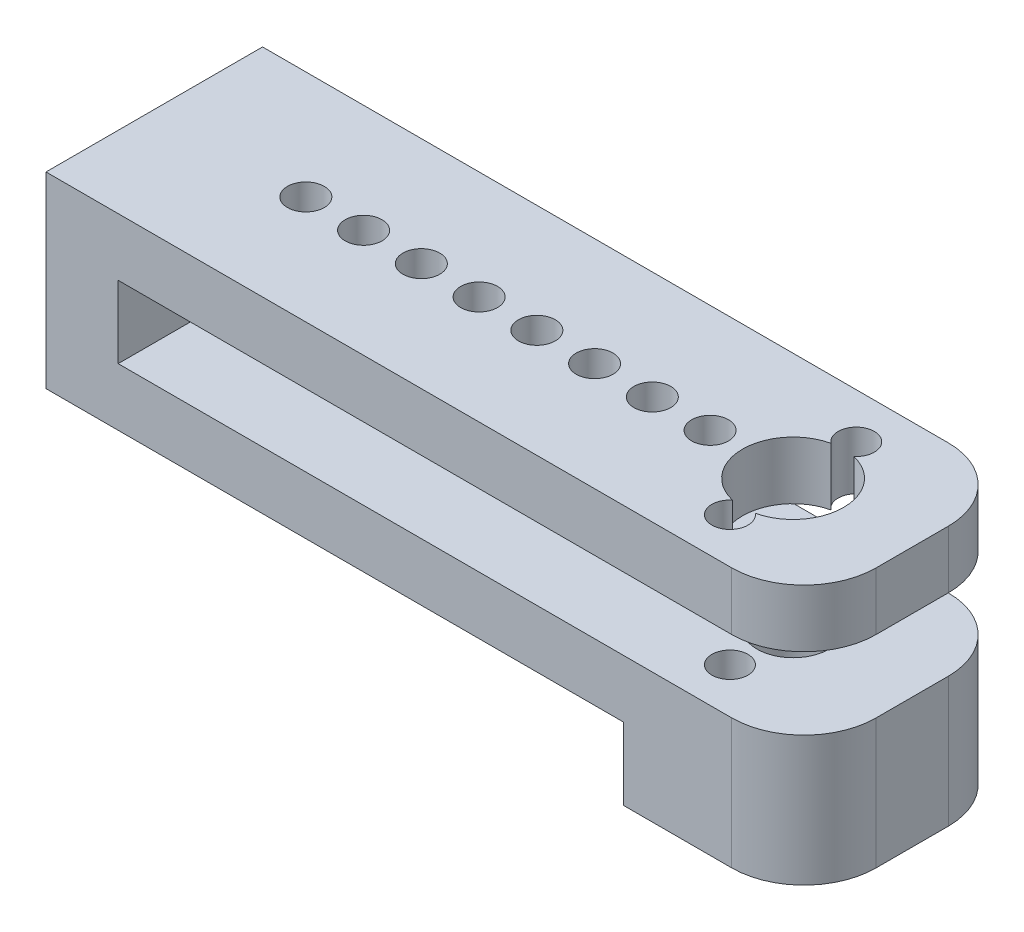
SolidWorks part; units mm, degrees
ref_plane "Front Plane" through (0, 0, 0) normal (0, 0, 1) x (1, 0, 0)
ref_plane "Top Plane" through (0, 0, 0) normal (0, 1, 0) x (1, 0, 0)
ref_plane "Right Plane" through (0, 0, 0) normal (1, 0, 0) x (0, 0, -1)
sketch "Sketch2" plane through (0, 0, 0) normal (0, 1, 0) x (1, 0, 0)
  line L1 (-72, 15) -> (3, 15)
  line L2 (-72, 15) -> (-72, -15)
  line L3 (-72, -15) -> (3, -15)
  line L4 (3, 15) -> (3, -15)
  dimension "D1" = 75
  dimension "D2" = 30
  dimension "D3" = 15
  dimension "D4" = 3
extrude "Boss-Extrude1" add sketch "Sketch2" along normal blind 8
sketch "Sketch3" plane through (0, 8, 0) normal (0, 1, 0) x (1, 0, 0)
  circle A0 centre (0, 0) radius 2.55
  dimension "D1" = 5.1
extrude "Cut-Extrude1" cut sketch "Sketch3" against normal offset from surface (7 mm away) 1 up to face at (-34.5, 0, 0)
sketch "Sketch4" plane through (0, 1, 0) normal (0, 1, 0) x (1, 0, 0)
  circle A0 centre (0, 0) radius 0.6
  dimension "D1" = 1.2
extrude "Cut-Extrude2" cut sketch "Sketch4" against normal blind 1
pattern_linear "LPattern3" count 8 spacing 8 along (-1, 0, 0) of "Cut-Extrude1", "Cut-Extrude2"
ref_plane "Plane1" through (0, -5, 0) normal (0, -1, 0) x (-1, 0, 0)
mirror "Mirror2" about plane through (0, -5, 0) normal (0, -1, 0) of bodies 122
sketch "Sketch5" plane through (-72, 0, 0) normal (-1, 0, 0) x (0, 0, 1)
  line L1 (-15, 8) -> (15, 8)
  line L2 (-15, 8) -> (-15, -18)
  line L3 (-15, -18) -> (15, -18)
  line L4 (15, 8) -> (15, -18)
extrude "Boss-Extrude2" add sketch "Sketch5" along normal blind 5 and the other way blind 5
sketch "Sketch6" plane through (3, 0, 0) normal (1, 0, 0) x (0, 0, -1)
  line L1 (-15, -10) -> (15, -10)
  line L2 (-15, -10) -> (-15, -18)
  line L3 (-15, -18) -> (15, -18)
  line L4 (15, -10) -> (15, -18)
extrude "Boss-Extrude3" add sketch "Sketch6" along normal blind 25
sketch "Sketch8" plane through (0, -18, 0) normal (0, -1, 0) x (1, 0, 0)
  line L0 (28, -15) -> (-77, -15) construction
  line L1 (28, 15) -> (3, 15)
  line L2 (28, 15) -> (28, -15)
  line L3 (28, -15) -> (3, -15)
  line L4 (3, 15) -> (3, -15)
  dimension "D1" = 25
extrude "Boss-Extrude4" add sketch "Sketch8" along normal blind 5
sketch "Sketch9" plane through (0, -23, 0) normal (0, -1, 0) x (1, 0, 0)
  line L0 (3, -15) -> (-77, -15) construction
  line L1 (28, 15) -> (-2, 15)
  line L2 (28, 15) -> (28, -15)
  line L3 (28, -15) -> (-2, -15)
  line L4 (-2, 15) -> (-2, -15)
  dimension "D1" = 30
extrude "Boss-Extrude5" add sketch "Sketch9" along normal blind 5 contours L4 L3 L2 L1
sketch "Sketch11" plane through (0, -28, 0) normal (0, -1, 0) x (1, 0, 0)
  circle A0 centre (11.5, 0) radius 11.1
  point P2 (0, 0)
  point P4 (0, 0)
  point P5 (0, 0)
  point P6 (0, 0)
  point P7 (11.2101, 2.55)
  dimension "D1" = 22.2
  dimension "D2" = 11.5
extrude "Cut-Extrude3" cut sketch "Sketch11" against normal blind 4 contours A0
sketch "Sketch13" plane through (0, -24, 0) normal (0, -1, 0) x (1, 0, 0)
  line L0 (11.5, 11.1) -> (11.5, -11.1) construction
  line L1 (0.4, 0) -> (22.6, 0) construction
  circle A0 centre (11.5, 8.75) radius 1.5
  circle A1 centre (11.5, 0) radius 11.1 construction
  circle A2 centre (11.5, 0) radius 11.1 construction
  circle A3 centre (11.5, -8.75) radius 1.5
  point P5 (0, 0)
  dimension "D1" = 3
  dimension "D2" = 17.5
extrude "Cut-Extrude4" cut sketch "Sketch13" against normal through all
sketch "Sketch16" plane through (3, 0, 0) normal (1, 0, 0) x (0, 0, -1)
  line L1 (-15, 8) -> (15, 8)
  line L2 (-15, 8) -> (-15, 0)
  line L3 (-15, 0) -> (15, 0)
  line L4 (15, 8) -> (15, 0)
extrude "Boss-Extrude6" add sketch "Sketch16" along normal blind 25
sketch "Sketch14" plane through (0, -10, 0) normal (0, 1, 0) x (1, 0, 0)
  circle A0 centre (11.5, 8.75) radius 2.5
  circle A1 centre (11.5, -8.75) radius 2.5
  dimension "D1" = 5
extrude "Cut-Extrude5" cut sketch "Sketch14" against normal offset from surface 1 and the other way through all up to face at (11.5, -24, 7.25)
sketch "Sketch15" plane through (0, -24, 0) normal (0, -1, 0) x (1, 0, 0)
  circle A0 centre (11.5, 0) radius 5
  dimension "D1" = 10
extrude "Cut-Extrude6" cut sketch "Sketch15" against normal through all
fillet "Fillet2" radius 10 2 edges at (28, -19, -15) (28, -19, 15)
fillet "Fillet3" radius 10 2 edges at (28, 4, -15) (28, 4, 15)
sketch "Sketch18" plane through (0, 8, 0) normal (0, 1, 0) x (1, 0, 0)
  circle A0 centre (11.5, 0) radius 7
  dimension "D1" = 14
extrude "Cut-Extrude7" cut sketch "Sketch18" against normal up to next contours A0
sketch "Sketch19" plane through (-67, 0, 0) normal (1, 0, 0) x (0, 0, -1)
  line L0 (-16.5, -5) -> (16.5, -5) construction
  circle A0 centre (0, -5) radius 1.5
  dimension "D1" = 3
extrude "Cut-Extrude8" cut sketch "Sketch19" against normal through all
sketch "Sketch21" plane through (-67, 0, 0) normal (1, 0, 0) x (0, 0, -1)
  line L0 (-16.5, -5) -> (16.5, -5) construction
  circle A0 centre (0, -5) radius 3.5
  dimension "D1" = 7
extrude "Cut-Extrude9" cut sketch "Sketch21" against normal blind 3
sketch "Sketch22" plane through (0, -18, 0) normal (0, -1, 0) x (1, 0, 0)
  line L1 (-2, 15) -> (3, 15)
  line L2 (-2, 15) -> (-2, -15)
  line L3 (-2, -15) -> (3, -15)
  line L4 (3, 15) -> (3, -15)
extrude "Cut-Extrude10" cut sketch "Sketch22" along normal through all
